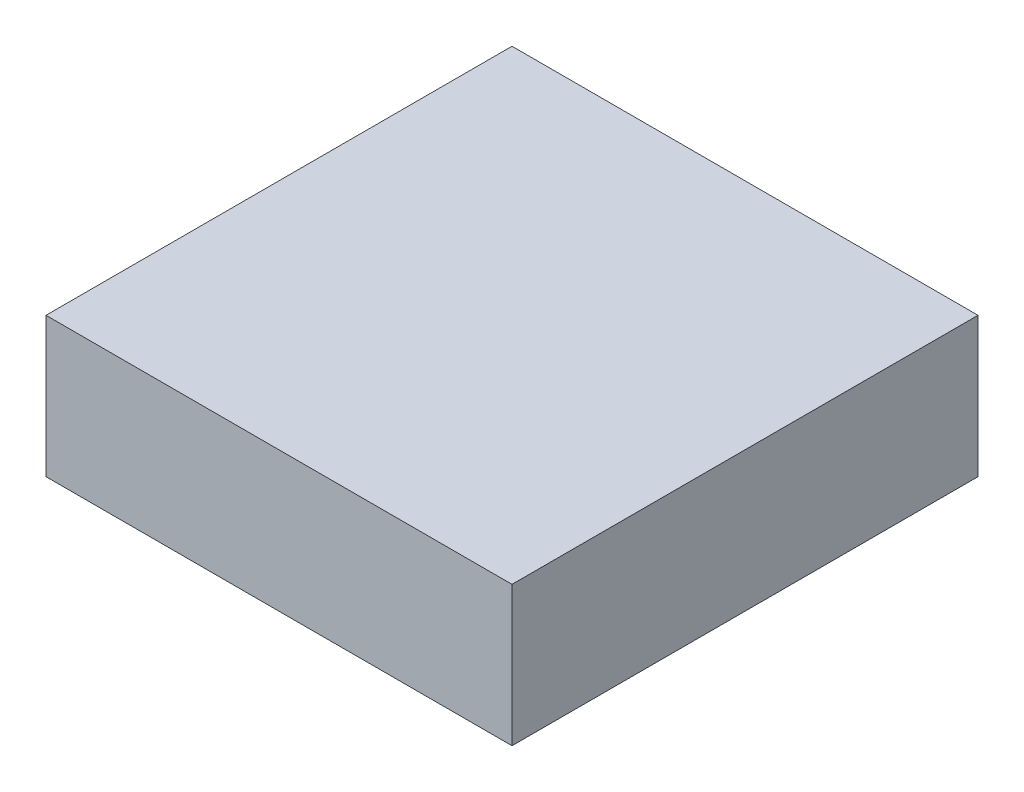
SolidWorks part; units mm, degrees
ref_plane "前视基准面" through (0, 0, 0) normal (0, 0, 1) x (1, 0, 0)
ref_plane "上视基准面" through (0, 0, 0) normal (0, 1, 0) x (1, 0, 0)
ref_plane "右视基准面" through (0, 0, 0) normal (1, 0, 0) x (0, 0, -1)
sketch "草图1" plane through (0, 0, 0) normal (0, 1, 0) x (1, 0, 0)
  line L1 (0, 0) -> (10, 0)
  line L2 (0, 0) -> (0, 10)
  line L3 (0, 10) -> (10, 10)
  line L4 (10, 0) -> (10, 10)
extrude "凸台-拉伸1" add sketch "草图1" along normal blind 3 contours L2 L3 L4 L1
sketch "草图2" plane through (0, 0, 0) normal (0, 1, 0) x (1, 0, 0)
  line L1 (0.7086, 9.2164) -> (1.5533, 9.2164)
  line L2 (0.7086, 9.2164) -> (0.7086, 8.4671)
  line L3 (0.7086, 8.4671) -> (1.5533, 8.4671)
  line L4 (1.5533, 9.2164) -> (1.5533, 8.4671)
  line L5 (4.2235, 9.2164) -> (5.2044, 9.2164)
  line L6 (4.2235, 9.2164) -> (4.2235, 8.4671)
  line L7 (4.2235, 8.4671) -> (5.2044, 8.4671)
  line L8 (5.2044, 9.2164) -> (5.2044, 8.4671)
  line L9 (0.8721, 1.3013) -> (2.0301, 1.3013)
  line L10 (0.8721, 1.3013) -> (0.8721, 0.4021)
  line L11 (0.8721, 0.4021) -> (2.0301, 0.4021)
  line L12 (2.0301, 1.3013) -> (2.0301, 0.4021)
  line L13 (7.5339, 9.2164) -> (9.305, 9.2164)
  line L14 (7.5339, 9.2164) -> (7.5339, 8.1538)
  line L15 (7.5339, 8.1538) -> (9.305, 8.1538)
  line L16 (9.305, 9.2164) -> (9.305, 8.1538)
  line L17 (3.2971, 7.2002) -> (4.5504, 7.2002)
  line L18 (3.2971, 7.2002) -> (3.2971, 5.5245)
  line L19 (3.2971, 5.5245) -> (4.5504, 5.5245)
  line L20 (4.5504, 7.2002) -> (4.5504, 5.5245)
  line L21 (5.8991, 6.6825) -> (6.3078, 6.6825)
  line L22 (5.8991, 6.6825) -> (5.8991, 4.6117)
  line L23 (5.8991, 4.6117) -> (6.3078, 4.6117)
  line L24 (6.3078, 6.6825) -> (6.3078, 4.6117)
  line L25 (3.2971, 4.2984) -> (4.7139, 4.2984)
  line L26 (3.2971, 4.2984) -> (3.2971, 3.1268)
  line L27 (3.2971, 3.1268) -> (4.7139, 3.1268)
  line L28 (4.7139, 4.2984) -> (4.7139, 3.1268)
  line L29 (6.3078, 2.8679) -> (4.7139, 2.8679)
  line L30 (6.3078, 2.8679) -> (6.3078, 1.6555)
  line L31 (6.3078, 1.6555) -> (4.7139, 1.6555)
  line L32 (4.7139, 2.8679) -> (4.7139, 1.6555)
extrude "切除-拉伸1" cut sketch "草图2" along normal blind 1
sketch "草图3" plane through (0, 0, 0) normal (0, 1, 0) x (1, 0, 0)
  line L1 (1.7587, 4.4579) -> (2.1104, 4.4579)
  line L2 (1.7587, 4.4579) -> (1.7587, 5.3176)
  line L3 (1.7587, 5.3176) -> (2.1104, 5.3176)
  line L4 (2.1104, 4.4579) -> (2.1104, 5.3176)
  line L5 (2.1104, 6.6268) -> (2.4816, 6.6268)
  line L6 (2.1104, 6.6268) -> (2.1104, 8.1704)
  line L7 (2.1104, 8.1704) -> (2.4816, 8.1704)
  line L8 (2.4816, 6.6268) -> (2.4816, 8.1704)
  line L9 (3.693, 7.7405) -> (5.1389, 7.7405)
  line L10 (3.693, 7.7405) -> (3.693, 8.1704)
  line L11 (3.693, 8.1704) -> (5.1389, 8.1704)
  line L12 (5.1389, 7.7405) -> (5.1389, 8.1704)
  line L13 (6.9756, 5.5717) -> (7.9917, 5.5717)
  line L14 (6.9756, 5.5717) -> (6.9756, 6.6268)
  line L15 (6.9756, 6.6268) -> (7.9917, 6.6268)
  line L16 (7.9917, 5.5717) -> (7.9917, 6.6268)
  line L17 (6.5653, 3.266) -> (7.679, 3.266)
  line L18 (6.5653, 3.266) -> (6.5653, 4.1062)
  line L19 (6.5653, 4.1062) -> (7.679, 4.1062)
  line L20 (7.679, 3.266) -> (7.679, 4.1062)
  line L21 (7.3078, 1.742) -> (8.3238, 1.742)
  line L22 (7.3078, 1.742) -> (7.3078, 2.6799)
  line L23 (7.3078, 2.6799) -> (8.3238, 2.6799)
  line L24 (8.3238, 1.742) -> (8.3238, 2.6799)
extrude "切除-拉伸3" cut sketch "草图3" along normal blind 1
